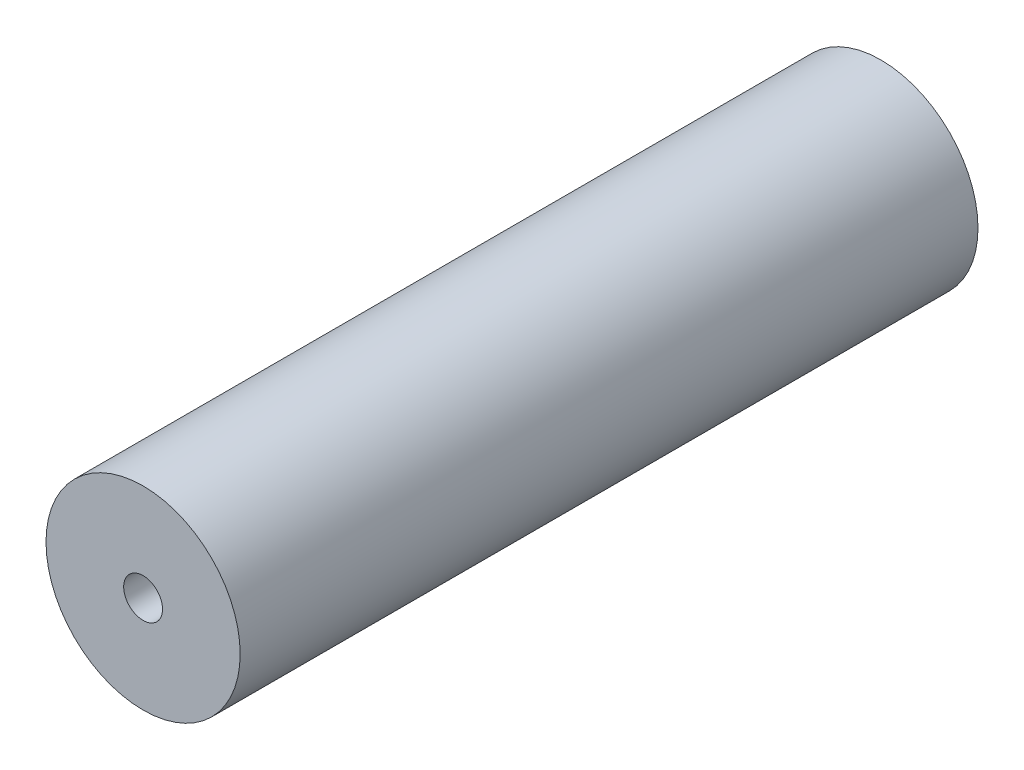
SolidWorks part; units mm, degrees
ref_plane "Plan de face" through (0, 0, 0) normal (0, 0, 1) x (1, 0, 0)
ref_plane "Plan de dessus" through (0, 0, 0) normal (0, 1, 0) x (1, 0, 0)
ref_plane "Plan de droite" through (0, 0, 0) normal (1, 0, 0) x (0, 0, -1)
sketch "Esquisse1" plane through (0, 0, 0) normal (0, 0, 1) x (1, 0, 0)
  circle A0 centre (0, 0) radius 25
  circle A1 centre (0, 0) radius 5
  dimension "D1" = 50
  dimension "D2" = 10
extrude "Boss.-Extru.1" add sketch "Esquisse1" along normal blind 190
